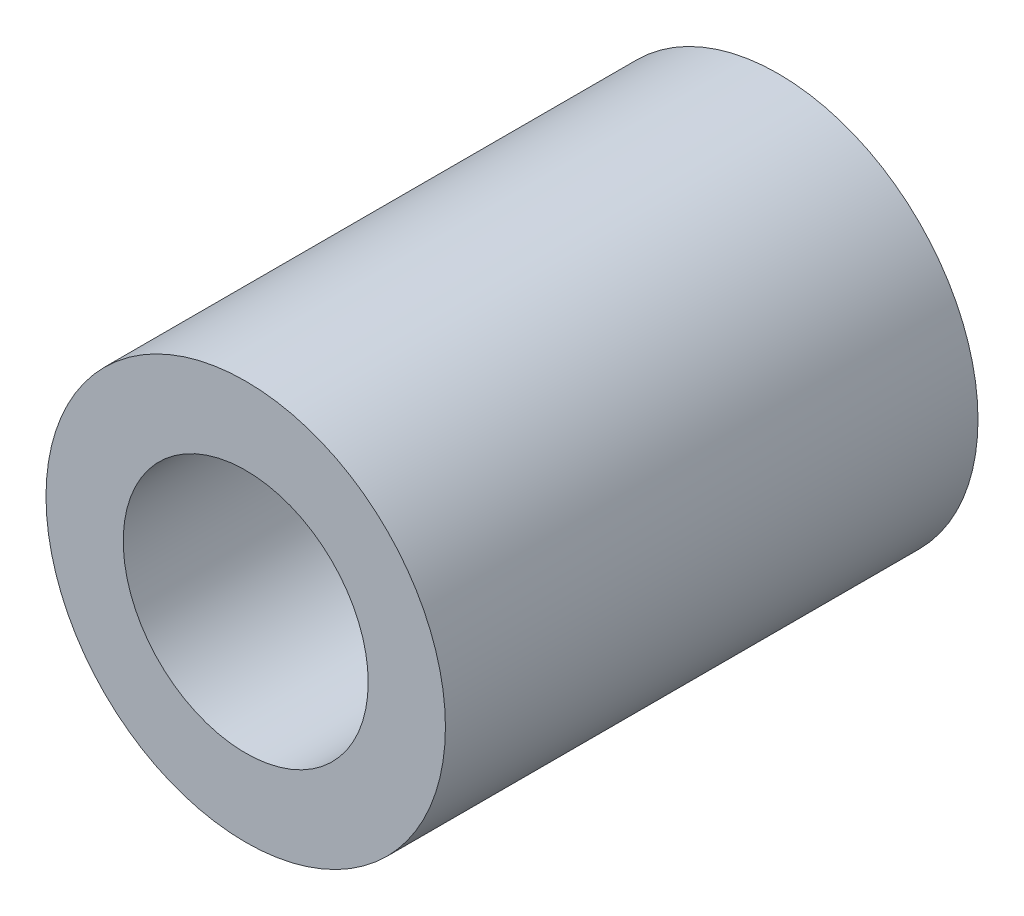
SolidWorks part; units mm, degrees
ref_plane "Front Plane" through (0, 0, 0) normal (0, 0, 1) x (1, 0, 0)
ref_plane "Top Plane" through (0, 0, 0) normal (0, 1, 0) x (1, 0, 0)
ref_plane "Right Plane" through (0, 0, 0) normal (1, 0, 0) x (0, 0, -1)
sketch "Sketch1" plane through (0, 0, 0) normal (0, 0, 1) x (1, 0, 0)
  line L0 (0, 1.4605) -> (0, 2.3813) construction
  line L1 (0, -1.4605) -> (0, -2.3813) construction
  circle A0 centre (0, 0) radius 2.3813
  circle A1 centre (0, 0) radius 1.4605
  dimension "OD" = 4.7625
  dimension "ID" = 2.921
sketch "Sketch2" plane through (0, 0, 0) normal (1, 0, 0) x (0, 0, -1)
  line L0 (-3.175, 1.4605) -> (3.175, 1.4605) construction
  line L1 (-3.175, -1.4605) -> (3.175, -1.4605) construction
  line L2 (-3.175, -2.3813) -> (3.175, -2.3813) construction
  line L3 (-3.175, 2.3813) -> (3.175, 2.3813) construction
  dimension "Length" = 6.35
extrude "Extrude1" add sketch "Sketch1" along normal up to vertex (3.175 mm away) and the other way up to vertex (3.175 mm away) up to point (0, 1.4605, 3.175) other way up to point (0, 1.4605, -3.175)
sketch "Sketch3" plane through (0, 0, 3.175) normal (0, 0, 1) x (1, 0, 0)
  circle A0 centre (0, 0) radius 1.4605 construction
  circle A3 centre (0, 0) radius 1.4605
  point P3 (-1.4605, 0)
